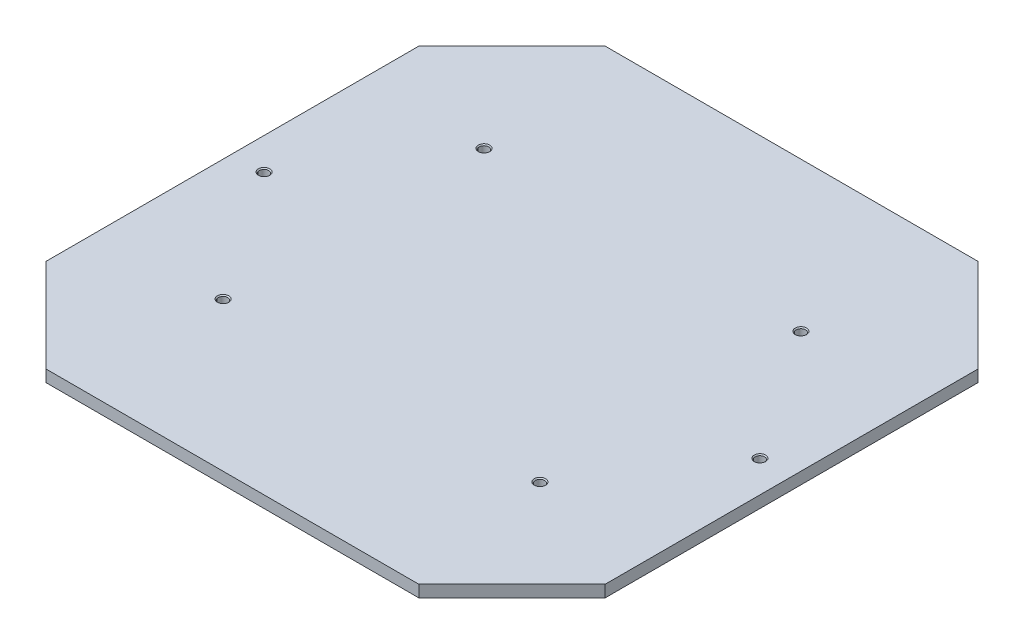
SolidWorks part; units mm, degrees
ref_plane "Front Plane" through (0, 0, 0) normal (0, 0, 1) x (1, 0, 0)
ref_plane "Top Plane" through (0, 0, 0) normal (0, 1, 0) x (1, 0, 0)
ref_plane "Right Plane" through (0, 0, 0) normal (1, 0, 0) x (0, 0, -1)
sketch "Sketch2" plane through (0, 0, 0) normal (0, 1, 0) x (1, 0, 0)
  line L1 (-75, -75) -> (75, -75)
  line L2 (-75, -75) -> (-75, 75)
  line L3 (-75, 75) -> (75, 75)
  line L4 (75, -75) -> (75, 75)
  line L5 (-75, -75) -> (75, 75) construction
  line L6 (-75, 75) -> (75, -75) construction
  point P0 (0, 0)
  dimension "D1" = 150
  dimension "D2" = 150
extrude "Boss-Extrude2" add sketch "Sketch2" along normal blind 3.175
sketch "Sketch3" plane through (0, 3.175, 0) normal (0, 1, 0) x (1, 0, 0)
  line L0 (-42.5, 75) -> (-42.5, -75) construction
  line L1 (75, 75) -> (-75, 75) construction
  line L2 (-75, -75) -> (75, -75) construction
  line L3 (-75, 35) -> (75, 35) construction
  line L4 (-75, 75) -> (-75, -75) construction
  line L5 (75, -75) -> (75, 75) construction
  line L6 (-75, 0) -> (75, 0) construction
  line L7 (0, 75) -> (0, -75) construction
  line L8 (42.5, 75) -> (42.5, -75) construction
  line L9 (-75, -35) -> (75, -35) construction
  line L10 (-66.5, 45.2821) -> (-66.5, -48.9954) construction
  line L11 (-75, 75) -> (-75, -75) construction
  line L12 (66.5, 45.2821) -> (66.5, -48.9954) construction
  circle A0 centre (-42.5, 35) radius 7.6335
  circle A2 centre (42.5, -35) radius 3.266
  circle A4 centre (42.5, 35) radius 10.436
  circle A5 centre (-42.5, -35) radius 13.4263
  circle A6 centre (-66.5, 0) radius 3.2029
  circle A7 centre (66.5, 0) radius 3.2029
  point P34 (0, 0)
  dimension "D1" = 32.5
  dimension "D2" = 40
  dimension "D3" = 8.5
chamfer "Chamfer1" distance 25 angle 45 4 edges at (-75, 1.5875, -75) (75, 1.5875, -75) (-75, 1.5875, 75) (75, 1.5875, 75)
hole_wizard "M3x0.5 Tapped Hole1" positions "Sketch4" profile "Sketch5" tap size "M3x0.5" standard "ANSI Metric" end condition through all
sketch "Sketch4" plane through (0, 3.175, 0) normal (0, 1, 0) x (1, 0, 0)
  point P0 (-42.5, 35)
  point P3 (42.5, 35)
  point P6 (-42.5, -35)
  point P9 (42.5, -35)
  point P12 (-66.5, 0)
  point P15 (66.5, 0)
sketch "Sketch5" plane through (-42.5, 3.175, -35) normal (1, 0, 0) x (0, 0, 1)
  line L0 (0, 0) -> (0, 3.175)
  line L1 (0, 3.175) -> (1.25, 3.175)
  line L2 (1.25, 3.175) -> (1.25, 0.275)
  line L3 (1.25, 0.275) -> (1.525, 0)
  line L5 (1.525, 0) -> (0, 0)
  line L6 (-1.25, 0.275) -> (-1.525, 0) construction
  line L11 (0, -6.35) -> (0, 107.95) construction
  dimension "Thread Major Dia." = 2.5
  dimension "Thru Tap Drill Depth" = 3.175
  dimension "Near C'Sink Dia." = 3.05
  dimension "Near C'Sink Angle" = 90
